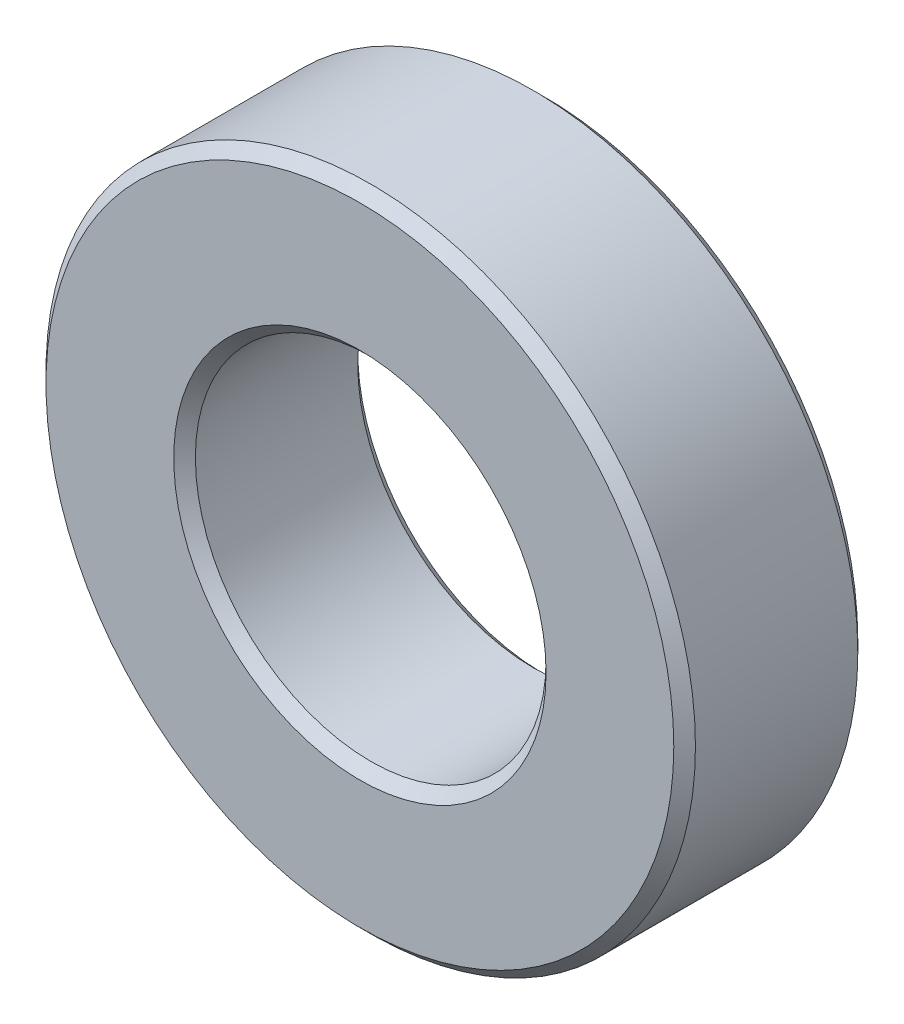
SolidWorks part; units mm, degrees
material "AISI 1020"
ref_plane "Face" through (0, 0, 0) normal (0, 0, 1) x (1, 0, 0)
ref_plane "Dessus" through (0, 0, 0) normal (0, 1, 0) x (1, 0, 0)
ref_plane "Droite" through (0, 0, 0) normal (1, 0, 0) x (0, 0, -1)
sketch "Esquisse1" plane through (0, 0, 0) normal (0, 0, 1) x (1, 0, 0)
  circle A0 centre (0, 0) radius 8.1
  circle A1 centre (0, 0) radius 15
extrude "Boss.-Extru.1" add sketch "Esquisse1" along normal blind 8.5
chamfer "Chanfrein1" distance 0.5 angle 45 4 edges at (8.1, 0, 0) (15, 0, 0) (8.1, 0, 8.5) (15, 0, 8.5)
